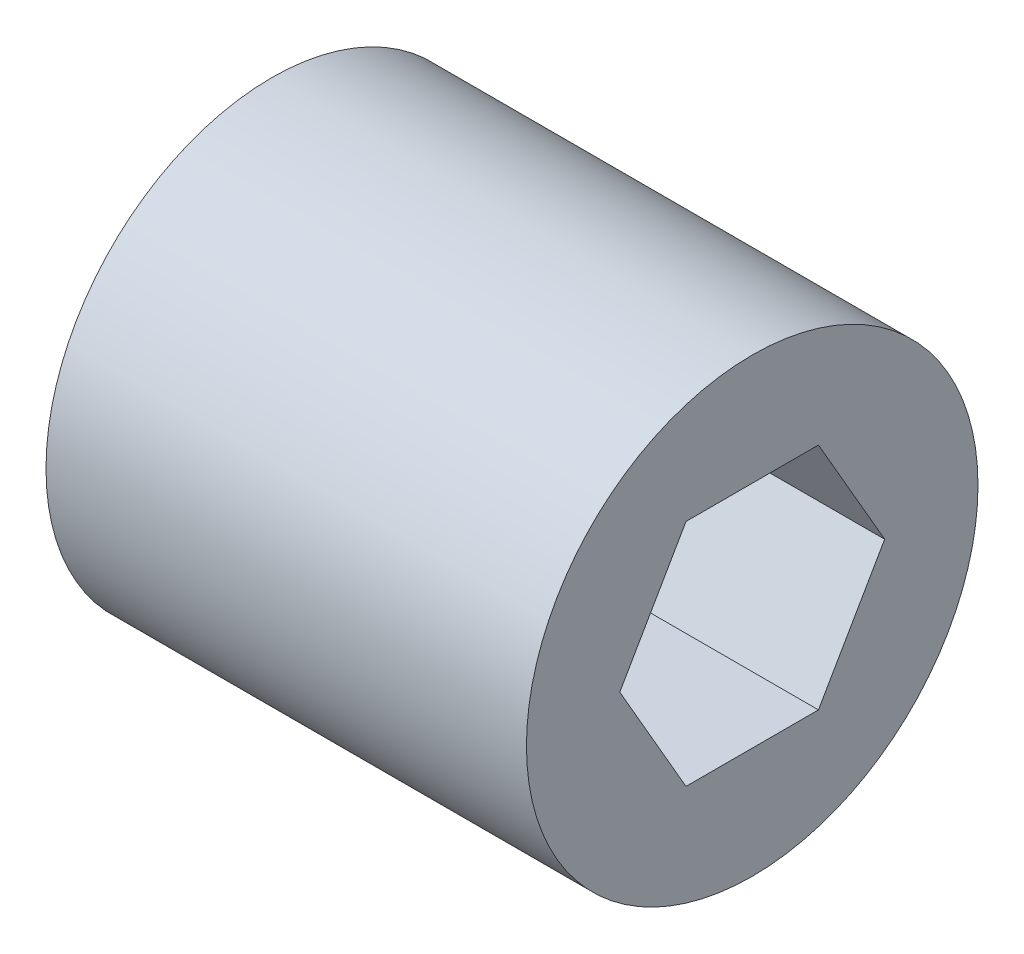
SolidWorks part; units mm, degrees
ref_plane "Alzado" through (0, 0, 0) normal (0, 0, 1) x (1, 0, 0)
ref_plane "Planta" through (0, 0, 0) normal (0, 1, 0) x (1, 0, 0)
ref_plane "Vista lateral" through (0, 0, 0) normal (1, 0, 0) x (0, 0, -1)
sketch "Croquis1" plane through (0, 0, 0) normal (1, 0, 0) x (0, 0, -1)
  line L1 (7.3323, 0) -> (3.6662, 6.35)
  line L2 (3.6662, 6.35) -> (-3.6662, 6.35)
  line L3 (-3.6662, 6.35) -> (-7.3323, 0)
  line L4 (-7.3323, 0) -> (-3.6662, -6.35)
  line L5 (-3.6662, -6.35) -> (3.6662, -6.35)
  line L6 (3.6662, -6.35) -> (7.3323, 0)
  circle A0 centre (0, 0) radius 6.35 construction
  circle A1 centre (0, 0) radius 12.5
  dimension "D2" = 25
  dimension "D1" = 12.7
extrude "Saliente-Extruir1" add sketch "Croquis1" along normal blind 26.6
